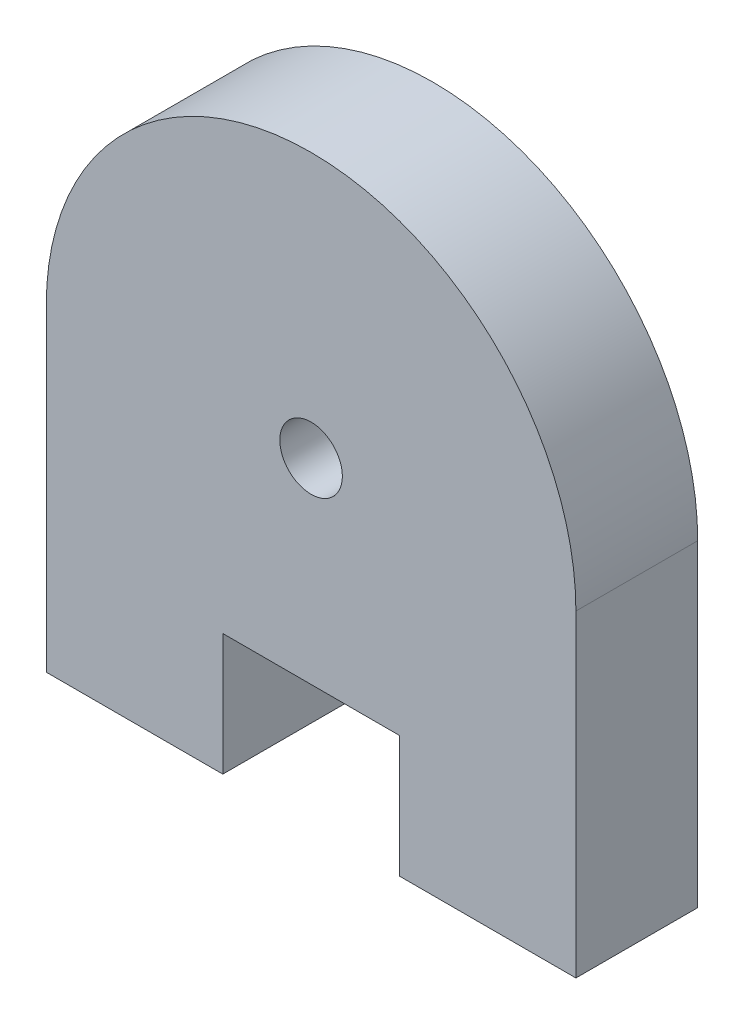
SolidWorks part; units mm, degrees
ref_plane "Front Plane" through (0, 0, 0) normal (0, 0, 1) x (1, 0, 0)
ref_plane "Top Plane" through (0, 0, 0) normal (0, 1, 0) x (1, 0, 0)
ref_plane "Right Plane" through (0, 0, 0) normal (1, 0, 0) x (0, 0, -1)
sketch "Sketch1" plane through (0, 0, 0) normal (0, 0, 1) x (1, 0, 0)
  line L0 (-15.1795, 5.715) -> (10.2205, 5.715) construction
  line L1 (10.2205, -9.525) -> (-15.1795, -9.525)
  line L2 (10.2205, -9.525) -> (10.2205, 5.715)
  line L4 (-15.1795, -9.525) -> (-15.1795, 5.715)
  arc A0 (10.2205, 5.715) -> (-15.1795, 5.715) centre (-2.4795, 5.715) ccw
  circle A1 centre (-2.4795, 5.715) radius 1.5
  point P0 (0, 0)
  dimension "D3" = 3
  dimension "D1" = 15.24
  dimension "D2" = 25.4
extrude "Boss-Extrude1" add sketch "Sketch1" along normal blind 5.842
sketch "Sketch3" plane through (0, 0, 5.842) normal (0, 0, 1) x (1, 0, 0)
  line L0 (-15.1795, -3.683) -> (10.2205, -3.683) construction
  line L1 (-15.1795, 5.715) -> (-15.1795, -9.525) construction
  line L2 (10.2205, -9.525) -> (10.2205, 5.715) construction
  line L3 (-15.1795, -9.525) -> (10.2205, -9.525) construction
  line L4 (-15.1795, -9.525) -> (-6.7129, -9.525) construction
  line L5 (1.7538, -9.525) -> (10.2205, -9.525) construction
  line L6 (-6.7129, -9.525) -> (1.7538, -9.525)
  line L7 (-6.7129, -9.525) -> (-6.7129, -3.683)
  line L8 (-6.7129, -3.683) -> (1.7538, -3.683)
  line L9 (1.7538, -9.525) -> (1.7538, -3.683)
  dimension "D1" = 5.842
extrude "Cut-Extrude2" cut sketch "Sketch3" against normal blind 5.842
